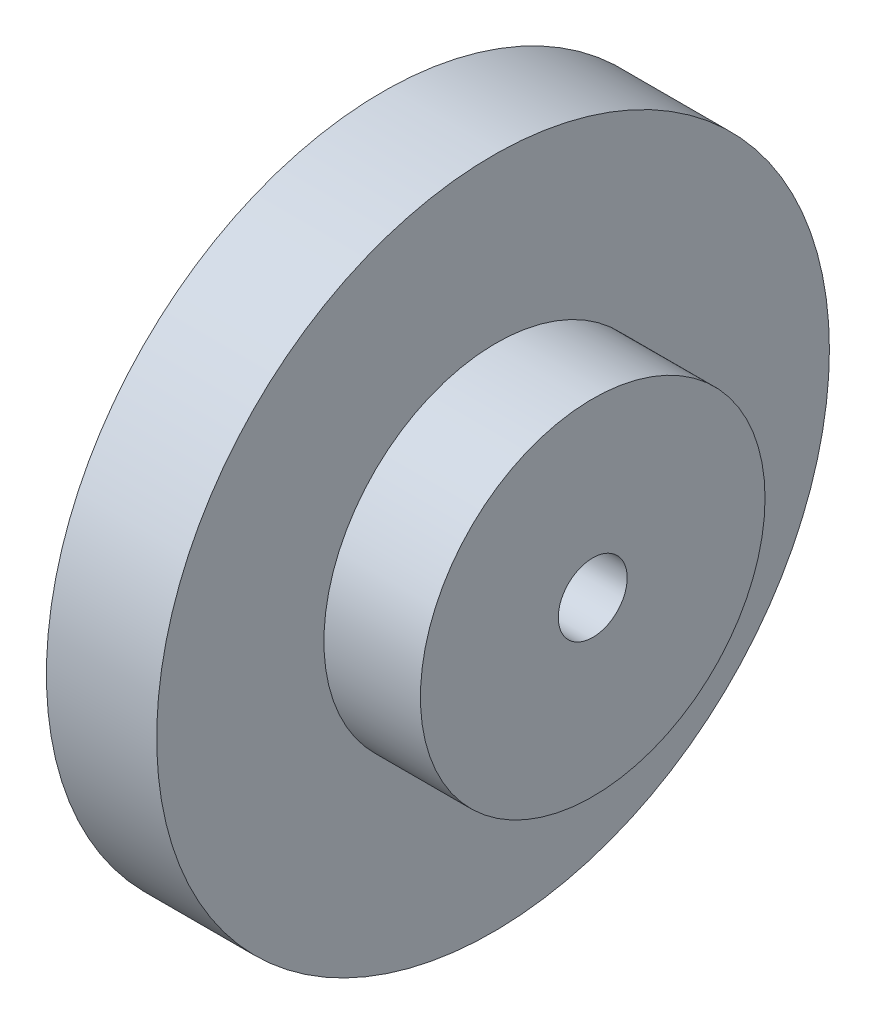
SolidWorks part; units mm, degrees
material "AISI 1035 Steel (SS)"
ref_plane "Front" through (0, 0, 0) normal (0, 0, 1) x (1, 0, 0)
ref_plane "Top" through (0, 0, 0) normal (0, 1, 0) x (1, 0, 0)
ref_plane "Right" through (0, 0, 0) normal (1, 0, 0) x (0, 0, -1)
sketch "Sketch1" plane through (0, 0, 0) normal (1, 0, 0) x (0, 0, -1)
  circle A0 centre (0, -0.1972) radius 24.4
  circle A1 centre (0.2308, -0.1972) radius 2.5
  dimension "D1" = 48.8
  dimension "D2" = 5
extrude "Boss-Extrude1" add sketch "Sketch1" along normal blind 8
sketch "Sketch2" plane through (8, 0, 0) normal (1, 0, 0) x (0, 0, -1)
  circle A0 centre (0.2308, -0.1972) radius 12.5
  circle A2 centre (0.2308, -0.1972) radius 2.5
  dimension "D1" = 25
  dimension "D2" = 5
extrude "Boss-Extrude3" add sketch "Sketch2" along normal blind 7
